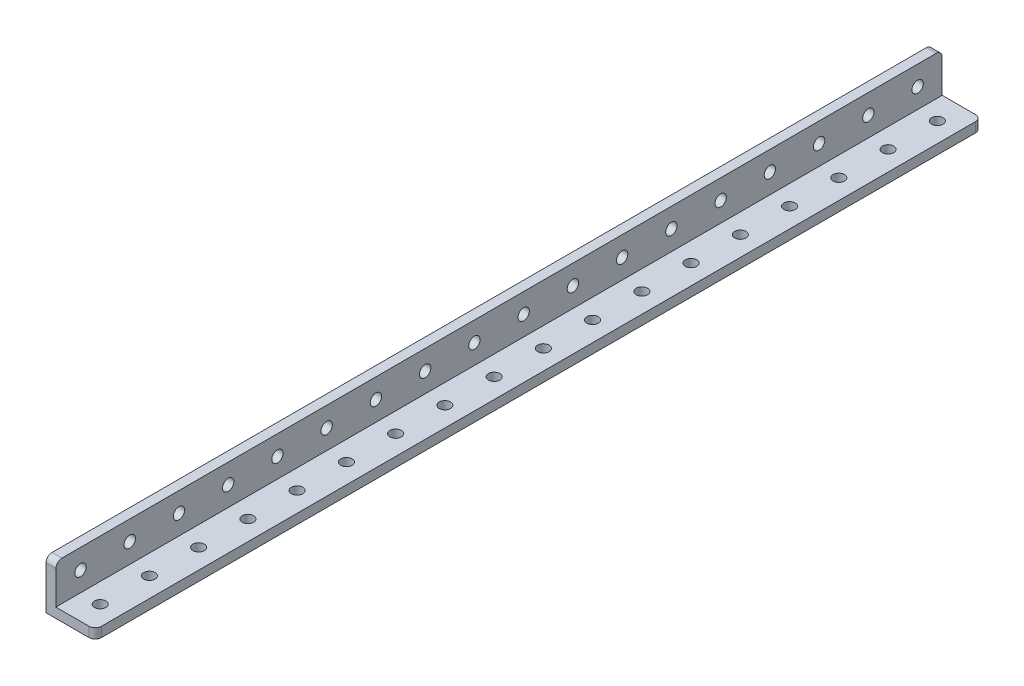
SolidWorks part; units mm, degrees
ref_plane "Front Plane" through (0, 0, 0) normal (0, 0, 1) x (1, 0, 0)
ref_plane "Top Plane" through (0, 0, 0) normal (0, 1, 0) x (1, 0, 0)
ref_plane "Right Plane" through (0, 0, 0) normal (1, 0, 0) x (0, 0, -1)
sketch "Sketch1" plane through (0, 0, 0) normal (0, 0, 1) x (1, 0, 0)
  line L0 (0, 16) -> (0, 0)
  line L1 (0, 0) -> (16, 0)
  line L2 (16, 0) -> (16, 3.2)
  line L3 (16, 3.2) -> (3.2, 3.2)
  line L4 (3.2, 3.2) -> (3.2, 16)
  line L5 (3.2, 16) -> (0, 16)
  dimension "D1" = 16
  dimension "D2" = 16
  dimension "D3" = 3.2
  dimension "D4" = 3.2
extrude "Boss-Extrude1" add sketch "Sketch1" against normal blind 288
sketch "Sketch2" plane through (0, 0, 0) normal (-1, 0, 0) x (0, 0, 1)
  line L0 (-154.1379, 9.6) -> (18.0301, 9.6) construction
  line L1 (-288, 0) -> (0, 0) construction
  line L2 (-72, 21.373) -> (-72, -6.9807) construction
  circle B0 centre (-88, 9.6) radius 1.85
  circle B1 centre (-104, 9.6) radius 1.85
  circle B2 centre (-120, 9.6) radius 1.85
  circle B3 centre (-136, 9.6) radius 1.85
  circle B4 centre (-8, 9.6) radius 1.85
  circle B5 centre (-24, 9.6) radius 1.85
  circle B6 centre (-40, 9.6) radius 1.85
  circle B7 centre (-56, 9.6) radius 1.85
  circle B8 centre (-72, 9.6) radius 1.85
  circle B9 centre (-232, 9.6241) radius 1.85
  circle B10 centre (-248, 9.6281) radius 1.85
  circle B11 centre (-264, 9.6321) radius 1.85
  circle B12 centre (-280, 9.6361) radius 1.85
  circle B13 centre (-152, 9.604) radius 1.85
  circle B14 centre (-168, 9.608) radius 1.85
  circle B15 centre (-184, 9.612) radius 1.85
  circle B16 centre (-200, 9.616) radius 1.85
  circle B17 centre (-216, 9.6201) radius 1.85
  dimension "D2" = 16
  dimension "D1" = 9.6
sketch_block_instance "Block1-1"
sketch_block "Block1"
sketch_block_instance "Block1-4"
extrude "Cut-Extrude1" cut sketch "Sketch2" against normal through all
sketch "Sketch3" plane through (0, 0, 0) normal (0, -1, 0) x (1, 0, 0)
  line L0 (9.6, 8.7023) -> (9.6, -150.3269) construction
  line L1 (0, -288) -> (0, 0) construction
  line L2 (-8.3353, -72) -> (37.7693, -72) construction
  circle B0 centre (9.6, -88) radius 1.85
  circle B1 centre (9.6, -104) radius 1.85
  circle B2 centre (9.6, -120) radius 1.85
  circle B3 centre (9.6, -136) radius 1.85
  circle B4 centre (9.6, -8) radius 1.85
  circle B5 centre (9.6, -24) radius 1.85
  circle B6 centre (9.6, -40) radius 1.85
  circle B7 centre (9.6, -56) radius 1.85
  circle B8 centre (9.6, -72) radius 1.85
  circle B9 centre (9.6, -232) radius 1.85
  circle B10 centre (9.6, -248) radius 1.85
  circle B11 centre (9.6, -264) radius 1.85
  circle B12 centre (9.6, -280) radius 1.85
  circle B13 centre (9.6, -152) radius 1.85
  circle B14 centre (9.6, -168) radius 1.85
  circle B15 centre (9.6, -184) radius 1.85
  circle B16 centre (9.6, -200) radius 1.85
  circle B17 centre (9.6, -216) radius 1.85
  dimension "D1" = 9.6
  dimension "D2" = 16
sketch_block_instance "Block1-2"
sketch_block_instance "Block1-6"
extrude "Cut-Extrude2" cut sketch "Sketch3" against normal through all
fillet "Fillet1" radius 2 4 edges at (1.6, 16, -288) (16, 1.6, -288) (16, 1.6, 0) (1.6, 16, 0)
